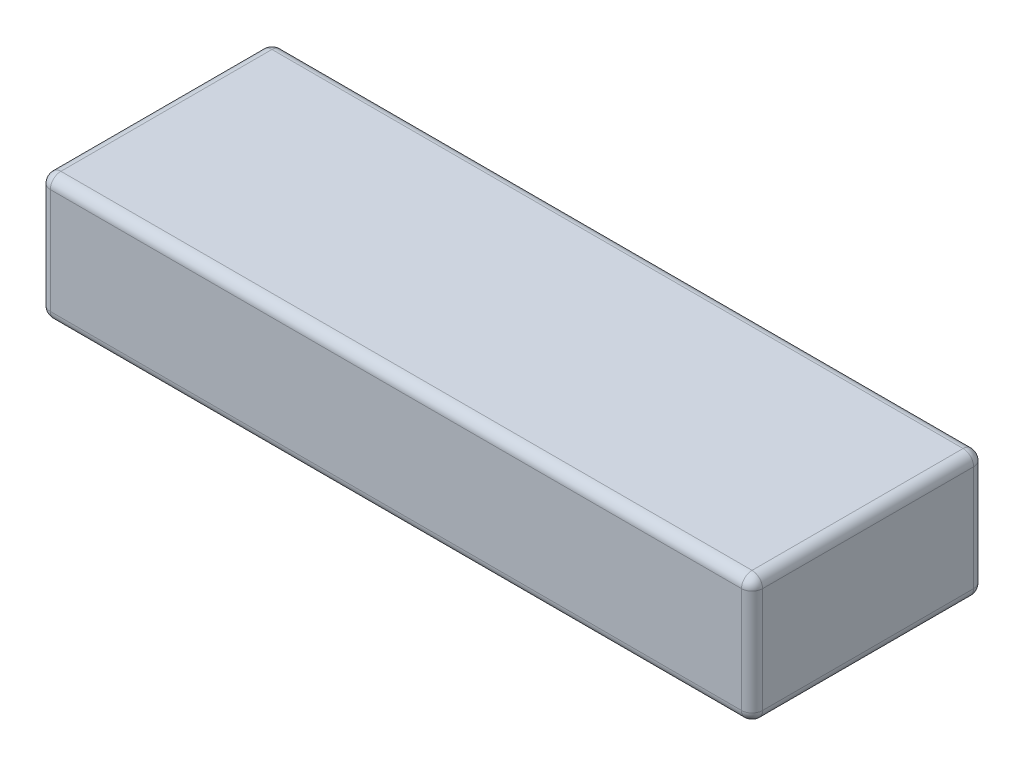
SolidWorks part; units mm, degrees
ref_plane "Спереди" through (0, 0, 0) normal (0, 0, 1) x (1, 0, 0)
ref_plane "Сверху" through (0, 0, 0) normal (0, 1, 0) x (1, 0, 0)
ref_plane "Справа" through (0, 0, 0) normal (1, 0, 0) x (0, 0, -1)
sketch "Эскиз1" plane through (0, 0, 0) normal (0, 1, 0) x (1, 0, 0)
  line L1 (-67.5, 22) -> (67.5, 22)
  line L2 (-67.5, 22) -> (-67.5, -22)
  line L3 (-67.5, -22) -> (67.5, -22)
  line L4 (67.5, 22) -> (67.5, -22)
  line L5 (-67.5, 22) -> (67.5, -22) construction
  line L6 (-67.5, -22) -> (67.5, 22) construction
  point P0 (0, 0)
  dimension "D1" = 135
  dimension "D2" = 44
extrude "Бобышка-Вытянуть1" add sketch "Эскиз1" along normal blind 24
fillet "Скругление1" radius 2 12 edges at (-67.5, 12, -22) (-67.5, 0, 0) (67.5, 12, -22) (67.5, 0, 0) (-67.5, 12, 22) (67.5, 12, 22) (0, 0, 22) (0, 24, 22) (-67.5, 24, 0) (0, 24, -22) (67.5, 24, 0) (0, 0, -22)
